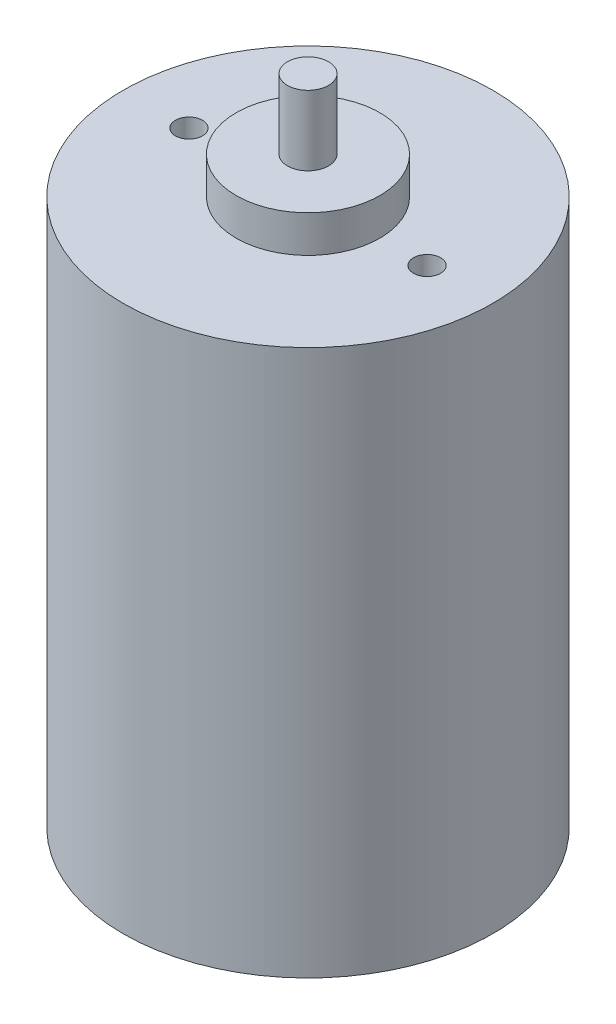
SolidWorks part; units mm, degrees
ref_plane "Front Plane" through (0, 0, 0) normal (0, 0, 1) x (1, 0, 0)
ref_plane "Top Plane" through (0, 0, 0) normal (0, 1, 0) x (1, 0, 0)
ref_plane "Right Plane" through (0, 0, 0) normal (1, 0, 0) x (0, 0, -1)
sketch "Sketch1" plane through (0, 0, 0) normal (0, 0, 1) x (1, 0, 0)
  line L0 (0, 8.7755) -> (0, -7.3214) construction
  line L1 (0, 0) -> (8.75, 0)
  line L2 (0, 0) -> (0, 4.5)
  line L3 (0, 4.5) -> (8.75, 4.5)
  line L4 (8.75, 0) -> (8.75, 4.5)
  line L5 (0, 13) -> (0, 4.5)
  line L6 (0, 0) -> (22.5, 0)
  line L7 (0, 0) -> (0, -66.5)
  line L8 (0, -66.5) -> (22.5, -66.5)
  line L9 (22.5, 0) -> (22.5, -66.5)
  line L10 (0, 4.5) -> (2.5, 4.5)
  line L11 (0, 4.5) -> (0, 13)
  line L12 (0, 13) -> (2.5, 13)
  line L13 (2.5, 4.5) -> (2.5, 13)
  dimension "D1" = 8.75
  dimension "D2" = 4.5
  dimension "D3" = 22.5
  dimension "D4" = 66.5
  dimension "D5" = 2.5
  dimension "D6" = 8.5
revolve "Revolve1" add sketch "Sketch1" angle 360 about L0
hole_wizard "Tap Drill for M4x0.7 Tap1" positions "Sketch4" profile "Sketch3" hole size "M4x0.7" standard "ANSI Metric"
sketch "Sketch4" plane through (0, 0, 0) normal (0, 1, 0) x (1, 0, 0)
  point P0 (-14.5, 0)
  point P2 (14.5, 0)
  dimension "D1" = 28.9999
  dimension "D2" = 14.5
sketch "Sketch3" plane through (-14.5, 0, 0) normal (1, 0, 0) x (0, 0, 1)
  line L0 (0, 0) -> (0, 7.3414)
  line L1 (0, 7.3414) -> (1.65, 6.35)
  line L2 (1.65, 6.35) -> (1.65, 0)
  line L5 (1.65, 0) -> (0, 0)
  line L10 (0, 7.3414) -> (-1.65, 6.35) construction
  line L11 (0, -6.35) -> (0, 107.95) construction
  dimension "Hole Dia." = 3.3
  dimension "Hole Depth" = 6.35
  dimension "Drill Angle" = 118
